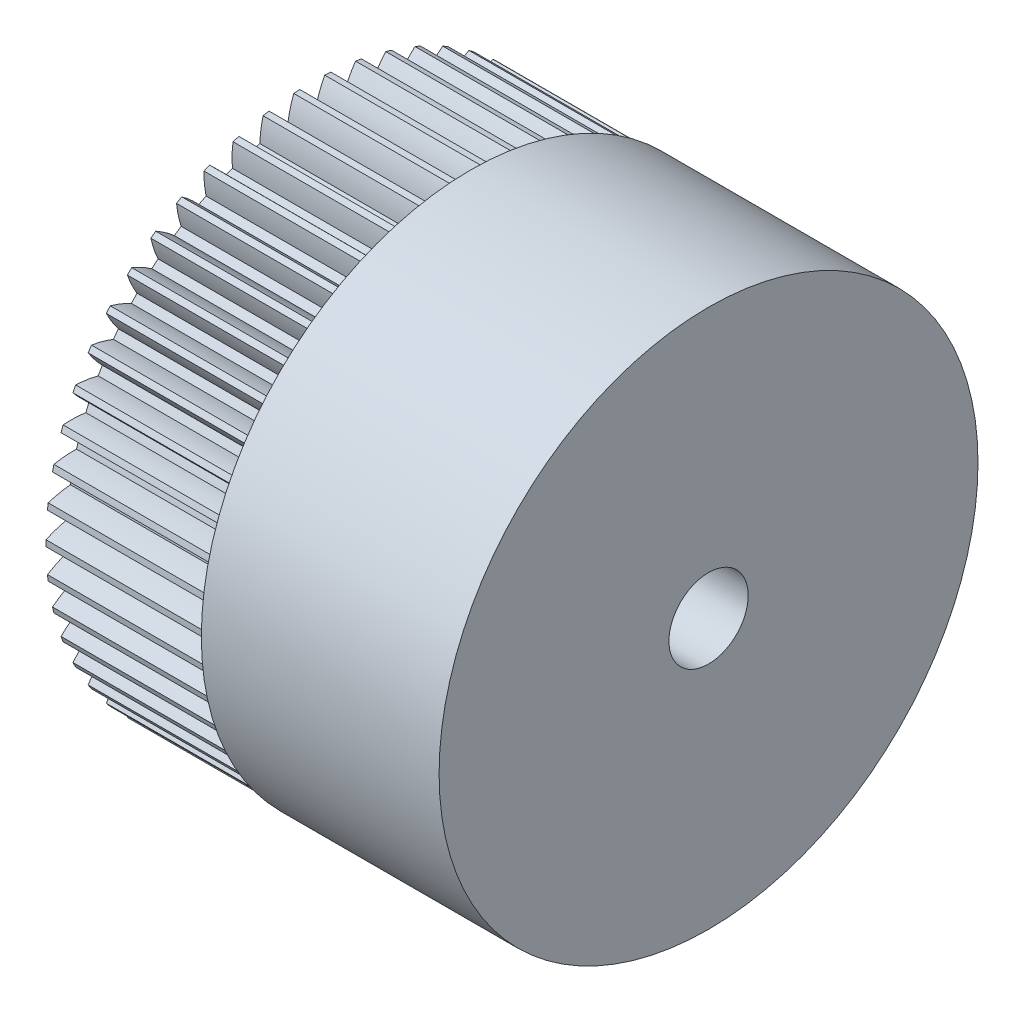
SolidWorks part; units mm, degrees
ref_plane "Plane1" through (0, 0, 0) normal (0, 0, 1) x (1, 0, 0)
ref_plane "Plane2" through (0, 0, 0) normal (0, 1, 0) x (1, 0, 0)
ref_plane "Plane3" through (0, 0, 0) normal (1, 0, 0) x (0, 0, -1)
other "Configuration Table"
sketch "HoldingSke" plane through (0, 0, 0) normal (0, 1, 0) x (1, 0, 0)
  line L0 (0, 0) -> (0.9796, -1.3484)
  line L1 (-15, 0) -> (100, 0) construction
  line L2 (0, 0) -> (-2.1039, 2.3779)
  line L3 (0, 0) -> (-11.863, 4.5341)
  line L4 (0, 0) -> (5.0761, 6.9867)
  line L5 (0, 0) -> (-46.8476, -17.4728)
  line L6 (0, 0) -> (-4.1448, -2.7965)
  line L7 (-2.1039, 2.3779) -> (8.6588, 51.2068)
  line L8 (-76.2, 54.61) -> (-75.7, 54.61)
  line L9 (-71.009, 38.7566) -> (-53.1078, 45.2721)
  line L10 (-76.2, 71.12) -> (104.1128, 71.12)
  line L11 (0, 0) -> (-5, 0)
  line L12 (-76.2, 101.6) -> (-76.177, 101.6)
  line L13 (24.9733, 27.94) -> (52.9518, 28.4284)
  line L14 (24.9733, 27.94) -> (24.9743, 27.94)
  line L15 (24.9733, 27.94) -> (100.4006, 29.5858)
  line L16 (-63.627, -0.6) -> (-12.827, -0.6)
  circle A0 centre (0, 0) radius 1.5
  circle A1 centre (0, 0) radius 15.449
  circle A2 centre (0, 0) radius 37.5
  circle A3 centre (0, 0) radius 1.5
  dimension "MHD" = 30.898
  dimension "Hub_dia" = 75
  dimension "Bore" = 3
  dimension "MBD" = 3
  dimension "Num_teeth" = 54
  dimension "Pitch" = 1.6667
  dimension "Overall_len" = 50
  dimension "Show_teeth" = 54
  dimension "Thickness" = 5
  dimension "OAL" = 50.001
  dimension "T_dim" = 0.5
  dimension "Ap" = 20
  dimension "H" = 19.05
  dimension "Pitch_radius" = 180.3128
  dimension "Width" = 5
  dimension "Backlash" = 0.023
  dimension "Addendum_fac" = 1
  dimension "Dedendum_fac" = 1.25
  dimension "Clearance_fac" = 0.25
  dimension "Dedendum_add" = 0.001
  dimension "Module" = 0.6
sketch "BasProSke" plane through (0, 0, 0) normal (0, 1, 0) x (1, 0, 0)
  line L0 (-10, 0) -> (60, 0) construction
  line L1 (0, 0) -> (0, 16.8)
  line L2 (0, 0) -> (10, 0)
  line L3 (10, 0) -> (10, 16.8)
  line L4 (10, 16.8) -> (0, 16.8)
  dimension "Thickness" = 10
  dimension "Diameter" = 33.6
revolve "Base-Revolve" add sketch "BasProSke" angle 360 about L0
sketch "TooCutSke" plane through (0, 0, 0) normal (1, 0, 0) x (0, 0, -1)
  line L1 (0, 0) -> (0, 107) construction
  line L2 (0, 0) -> (-0.5114, 16.1919) construction
  line L3 (0, 0) -> (-1.8832, 32.3337) construction
  line L4 (-0.5114, 16.1919) -> (-0.9416, 16.1669) construction
  arc A0 (0.2608, 15.4468) -> (-0.2608, 15.4468) centre (0, 0) ccw
  arc A1 (0.7988, 16.8064) -> (-0.7988, 16.8064) centre (0, 0) ccw
  circle A2 centre (0, 0) radius 16.2 construction
  circle A3 centre (0, 0) radius 15.223 construction
  arc A4 (-0.2608, 15.4468) -> (-0.7988, 16.8064) centre (-6.5168, 13.7576) ccw
  arc A5 (0.7988, 16.8064) -> (0.2608, 15.4468) centre (6.5168, 13.7576) ccw
  dimension "Root_dia" = 30.898
  dimension "Overcut_dia" = 33.6508
  dimension "Pitch_dia" = 32.4
  dimension "Base_dia" = 30.446
  dimension "Flank_rad" = 6.48
  dimension "Half_ang" = 3.333
  dimension "Half_CT" = 0.4309
extrude "ToothCut" cut sketch "TooCutSke" along normal through all
fillet "Breaks" [suppressed] radius 0.012
fillet "RootFillets" [suppressed] radius 0.151
pattern_circular "TeethCuts" count 54 every 6.667 about axis through (-10, 0, 0) along (1, 0, 0) of "ToothCut", "RootFillets", "Breaks"
sketch "HubNeaOneSke" plane through (0, 0, 0) normal (-1, 0, 0) x (0, 0, 1)
  circle A0 centre (0, 0) radius 15.449
  dimension "Diameter" = 30.898
extrude "HubNearOne" [suppressed] add sketch "HubNeaOneSke" along normal blind 40.001
sketch "HubNeaBotSke" plane through (0, 0, 0) normal (-1, 0, 0) x (0, 0, 1)
  circle A0 centre (0, 0) radius 15.449
  dimension "Diameter" = 30.898
extrude "HubNearBoth" [suppressed] add sketch "HubNeaBotSke" along normal blind 20.0005
ref_plane "FarPln" through (10, 0, 0) normal (1, 0, 0) x (0, 0, -1)
sketch "HubFarSke" plane through (10, 0, 0) normal (1, 0, 0) x (0, 0, -1)
  circle A0 centre (0, 0) radius 15.449
  dimension "Diameter" = 30.898
extrude "HubFar" [suppressed] add sketch "HubFarSke" along normal blind 20.0005
sketch "BorSke" plane through (0, 0, 0) normal (1, 0, 0) x (0, 0, -1)
  circle A0 centre (0, 0) radius 2
  dimension "Diameter" = 4
extrude "Bore" cut sketch "BorSke" along normal mid plane 100.0019
sketch "KeySke" plane through (0, 0, 0) normal (1, 0, 0) x (0, 0, -1)
  line L0 (-0.6, 0) -> (-0.6, 2)
  line L1 (-0.6, 2) -> (0.6, 2)
  line L2 (0.6, 2) -> (0.6, 0)
  line L3 (0, 0) -> (0, 34) construction
  line L4 (-0.6, 0) -> (0.6, 0)
  dimension "Offset" = 2
  dimension "Width" = 1.2
extrude "Keyway" [suppressed] cut sketch "KeySke" along normal mid plane 100.0019
pattern_circular "Keyway2" [suppressed] count 2 every 90 about axis through (-10, 0, 0) along (1, 0, 0)
sketch "Sketch1" plane through (10, 0, 0) normal (1, 0, 0) x (0, 0, -1)
  circle A0 centre (0, 0) radius 17
  circle A1 centre (0, 0) radius 2
  dimension "D1" = 34
  dimension "D2" = 4
extrude "Boss-Extrude1" add sketch "Sketch1" along normal blind 15
sketch "Sketch2" plane through (25, 0, 0) normal (1, 0, 0) x (0, 0, -1)
  circle A0 centre (0, 0) radius 2.5
  dimension "D1" = 5
extrude "Cut-Extrude1" cut sketch "Sketch2" against normal blind 5
equation "' \"Module@HoldingSke\" = 6.35"
equation "' \"Num_teeth@HoldingSke\" = 12"
equation "' \"Ap@HoldingSke\" =  20"
equation "' \"Ap@HoldingSke\" = 20"
equation "'\"Width@HoldingSke\" = 0.5 * 25.4"
equation "' \"Hub_dia@HoldingSke\"= 1 * 25.4"
equation "' \"Hub_dia@HoldingSke\" = 1 * 25.4"
equation "' \"Overall_len@HoldingSke\" = 1.0 * 25.4"
equation "' \"Bore@HoldingSke\" = 0.75 * 25.4"
equation "' \"T_dim@HoldingSke\" = 0.1 * 25.4"
equation "' \"Width@KeySke\" = 0.25 * 25.4"
equation "' \"Show_teeth@HoldingSke\" = 13"
equation "' \"Backlash@HoldingSke\" = 0.009 * 25.4"
equation "' \"Addendum_fac@HoldingSke\" = 1.0"
equation "' \"Dedendum_fac@HoldingSke\" = 1.25"
equation "' \"Dedendum_add@HoldingSke\" = 0.00005 * 25.4"
equation "' \"Clearance_fac@HoldingSke\" = 0.25"
equation "\"Pitch@HoldingSke\" = 1 / \"Module@HoldingSke\""
equation "\"Overcut_dia@TooCutSke\" = (\"Num_teeth@HoldingSke\" + 2 * \"Addendum_fac@HoldingSke\") / \"Pitch@HoldingSke\" + 0.002 * 25.4"
equation "\"Pitch_dia@TooCutSke\" = \"Num_teeth@HoldingSke\" / \"Pitch@HoldingSke\""
equation "\"Base_dia@TooCutSke\" = \"Num_teeth@HoldingSke\" / \"Pitch@HoldingSke\" * cos((\"Ap@HoldingSke\"  * 3.14159265 / 180))"
equation "\"Root_dia@TooCutSke\" = (\"Num_teeth@HoldingSke\" + 2) / \"Pitch@HoldingSke\" - 2 * (\"Addendum_fac@HoldingSke\" + \"Dedendum_fac@HoldingSke\") / \"Pitch@HoldingSke\" - \"Dedendum_add@HoldingSke\" * 2"
equation "\"Half_ang@TooCutSke\" = 180 / \"Num_teeth@HoldingSke\""
equation "\"Half_CT@TooCutSke\" = \"Num_teeth@HoldingSke\" / \"Pitch@HoldingSke\" * sin((3.14159265 / 2 / \"Num_teeth@HoldingSke\")) / 2 - 7 * \"Backlash@HoldingSke\" / 4"
equation "\"Flank_rad@TooCutSke\" = \"Num_teeth@HoldingSke\" / \"Pitch@HoldingSke\" / 5"
equation "\"Radius@RootFillets\" = \"Clearance_fac@HoldingSke\" / \"Pitch@HoldingSke\" + \"Dedendum_add@HoldingSke\""
equation "\"Break_rad@Breaks\" = 0.02 / \"Pitch@HoldingSke\""
equation "\"Thickness@HoldingSke\"= \"Width@HoldingSke\""
equation "\"OAL@HoldingSke\" = \"Thickness@HoldingSke\""
equation "\"MHD@HoldingSke\" = (\"Num_teeth@HoldingSke\" + 2) / \"Pitch@HoldingSke\" - 2 * (\"Addendum_fac@HoldingSke\" + \"Dedendum_fac@HoldingSke\")  / \"Pitch@HoldingSke\" - \"Dedendum_add@HoldingSke\" * 2"
equation "\"MBD@HoldingSke\" = (\"Num_teeth@HoldingSke\" + 2) / \"Pitch@HoldingSke\" - 2 * (\"Addendum_fac@HoldingSke\" + \"Dedendum_fac@HoldingSke\")  / \"Pitch@HoldingSke\" - \"Dedendum_add@HoldingSke\" * 2 - 0.002 * 25.4"
equation "\"MHD@HoldingSke\" = ((sgn( \"MHD@HoldingSke\" - \"Hub_dia@HoldingSke\" )-1)*( \"MHD@HoldingSke\" - \"Hub_dia@HoldingSke\" ))/-2+ \"Hub_dia@HoldingSke\""
equation "\"MBD@HoldingSke\" = ((sgn( \"MBD@HoldingSke\" - \"Bore@HoldingSke\" )-1)*( \"MBD@HoldingSke\" - \"Bore@HoldingSke\" ))/-2+ \"Bore@HoldingSke\""
equation "\"OAL@HoldingSke\" = ((sgn( \"OAL@HoldingSke\" - \"Overall_len@HoldingSke\" )+1)*( \"OAL@HoldingSke\" - \"Overall_len@HoldingSke\" ))/2 + \"Overall_len@HoldingSke\" + 0.000002 * 25.4"
equation "\"Num_teeth@TeethCuts\" = int( \"Show_teeth@HoldingSke\" ) + 1"
equation "\"Num_teeth@TeethCuts\" = ((sgn( \"Num_teeth@TeethCuts\" - \"Num_teeth@HoldingSke\" )-1)*( \"Num_teeth@TeethCuts\" - \"Num_teeth@HoldingSke\" ))/-2+ \"Num_teeth@HoldingSke\""
equation "\"Num_teeth@TeethCuts\" = ((sgn( \"Num_teeth@TeethCuts\" - 2.0)+1)*( \"Num_teeth@TeethCuts\" - 2.0))/2 +2.0"
equation "\"Angle@TeethCuts\" = 360.0 / \"Num_teeth@HoldingSke\""
equation "\"Diameter@BasProSke\" = (\"Num_teeth@HoldingSke\" + 2 * \"Addendum_fac@HoldingSke\") / \"Pitch@HoldingSke\""
equation "' \"Fillet_rad@BasProSke\" =  \"Thickness@HoldingSke\" * 0.05"
equation "' \"Fillet_rad@BasProSke\" = \"Thickness@HoldingSke\" * 0.05"
equation "\"MHD@HoldingSke\" = ((sgn( \"MHD@HoldingSke\" - \"Root_dia@TooCutSke\" )-1)*( \"MHD@HoldingSke\" - \"Root_dia@TooCutSke\" ))/-2+ \"Root_dia@TooCutSke\""
equation "\"Diameter@HubNeaOneSke\" = \"MHD@HoldingSke\""
equation "\"Length@HubNearOne\" = \"OAL@HoldingSke\" - \"Thickness@BasProSke\""
equation "\"Diameter@HubNeaBotSke\" = \"MHD@HoldingSke\""
equation "\"Length@HubNearBoth\" = ( \"OAL@HoldingSke\" - \"Thickness@BasProSke\" ) / 2.0"
equation "\"Thickness@FarPln\" = \"Thickness@BasProSke\""
equation "\"Diameter@HubFarSke\" = \"MHD@HoldingSke\""
equation "\"Length@HubFar\" = ( \"OAL@HoldingSke\" - \"Thickness@BasProSke\" ) / 2.0"
equation "\"D1@Bore\" = \"OAL@HoldingSke\" * 2.0"
equation "\"D1@Keyway\" = \"OAL@HoldingSke\" * 2.0"
equation "\"Offset@KeySke\" = \"T_dim@HoldingSke\" + \"MBD@HoldingSke\" / 2.0"
